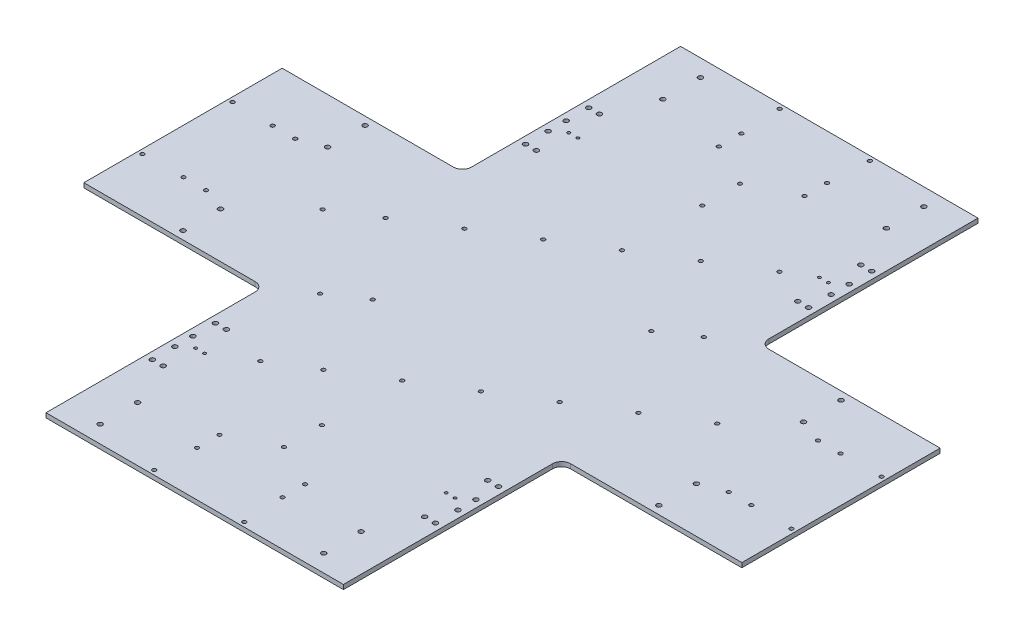
SolidWorks part; units mm, degrees
material "3.0205 (EN-AW 1200)"
ref_plane "前视基准面" through (0, 0, 0) normal (0, 0, 1) x (1, 0, 0)
ref_plane "上视基准面" through (0, 0, 0) normal (0, 1, 0) x (1, 0, 0)
ref_plane "右视基准面" through (0, 0, 0) normal (1, 0, 0) x (0, 0, -1)
other "Configuration Table"
sketch "Sketch1" plane through (0, 0, 0) normal (0, 1, 0) x (1, 0, 0)
  line L0 (165, 352) -> (-165, 352)
  line L1 (-165, 352) -> (-165, 110)
  line L2 (-165, 110) -> (-365, 110)
  line L5 (-365, 110) -> (-365, -110)
  line L6 (0, 352) -> (0, -66.8675) construction
  line L7 (-365, 0) -> (131.0517, 0) construction
  line L8 (365, 110) -> (365, -110)
  line L11 (165, 110) -> (365, 110)
  line L12 (165, 352) -> (165, 110)
  line L13 (165, -352) -> (165, -110)
  line L14 (165, -110) -> (365, -110)
  line L19 (-165, -110) -> (-365, -110)
  line L20 (-165, -352) -> (-165, -110)
  line L21 (165, -352) -> (-165, -352)
  point P21 (365, 0)
  dimension "D1" = 165
  dimension "D2" = 200
  dimension "D3" = 110
  dimension "D4" = 242
extrude "Boss-Extrude1" add sketch "Sketch1" along normal blind 5
sketch "Sketch2" plane through (0, 5, 0) normal (0, 1, 0) x (1, 0, 0)
  line L2 (365, 110) -> (165, 110) construction
  line L3 (365, -110) -> (365, 110) construction
  line L4 (-56.7455, 0) -> (47.5165, 0) construction
  line L5 (0, 54.7142) -> (0, -64.2255) construction
  line L7 (165, 352) -> (-165, 352) construction
  circle A0 centre (315, 49.5) radius 2.125
  circle A1 centre (290, 49.5) radius 2.125
  circle A7 centre (290, -49.5) radius 2.125
  circle A8 centre (315, -49.5) radius 2.125
  circle A9 centre (-315, -49.5) radius 2.125
  circle A10 centre (-290, -49.5) radius 2.125
  circle A13 centre (-290, 49.5) radius 2.125
  circle A14 centre (-315, 49.5) radius 2.125
  circle A15 centre (47.5, 302) radius 2.125
  circle A16 centre (47.5, 277) radius 2.125
  circle A17 centre (-47.5, 277) radius 2.125
  circle A18 centre (-47.5, 302) radius 2.125
  circle A19 centre (-47.5, -302) radius 2.125
  circle A20 centre (-47.5, -277) radius 2.125
  circle A21 centre (47.5, -277) radius 2.125
  circle A22 centre (47.5, -302) radius 2.125
  dimension "D1" = 60.5
  dimension "D5" = 4.25
  dimension "D7" = 4.25
  dimension "D9" = 4.25
  dimension "D10" = 4.25
  dimension "D4" = 25
  dimension "D6" = 50
  dimension "D11" = 47.5
  dimension "D12" = 50
  dimension "D13" = 25
extrude "Cut-Extrude1" cut sketch "Sketch2" against normal blind 3
sketch "Sketch4" plane through (0, 5, 0) normal (0, 1, 0) x (1, 0, 0)
  line L0 (-165, 352) -> (-165, 110) construction
  line L1 (165, 352) -> (-165, 352) construction
  line L2 (0, 46.9886) -> (0, -40.2904) construction
  line L3 (-35.103, 0) -> (92.4951, 0) construction
  line L5 (165, -352) -> (165, -110) construction
  circle A0 centre (-157, 172) radius 2.6
  circle A1 centre (-145, 172) radius 2.6
  circle A2 centre (-157, 197) radius 2.6
  circle A3 centre (-157, 217) radius 2.6
  circle A4 centre (-157, 242) radius 2.6
  circle A5 centre (-145, 242) radius 2.6
  circle A6 centre (145, 242) radius 2.6
  circle A7 centre (157, 242) radius 2.6
  circle A8 centre (157, 217) radius 2.6
  circle A9 centre (157, 197) radius 2.6
  circle A10 centre (145, 172) radius 2.6
  circle A11 centre (157, 172) radius 2.6
  circle A12 centre (157, -172) radius 2.6
  circle A13 centre (145, -172) radius 2.6
  circle A14 centre (157, -197) radius 2.6
  circle A15 centre (157, -217) radius 2.6
  circle A16 centre (157, -242) radius 2.6
  circle A17 centre (145, -242) radius 2.6
  circle A18 centre (-145, -242) radius 2.6
  circle A19 centre (-157, -242) radius 2.6
  circle A20 centre (-157, -217) radius 2.6
  circle A21 centre (-157, -197) radius 2.6
  circle A22 centre (-145, -172) radius 2.6
  circle A23 centre (-157, -172) radius 2.6
  circle A24 centre (144, -207) radius 1.6
  circle A25 centre (-144, -207) radius 1.6
  circle A26 centre (144, 207) radius 1.6
  circle A27 centre (-144, 207) radius 1.6
  circle A28 centre (134, -207) radius 1.6
  circle A29 centre (-134, -207) radius 1.6
  circle A30 centre (134, 207) radius 1.6
  circle A31 centre (-134, 207) radius 1.6
  dimension "D3" = 5.2
  dimension "D4" = 5.2
  dimension "D5" = 8
  dimension "D6" = 8
  dimension "D9" = 5.2
  dimension "D10" = 5.2
  dimension "D11" = 5.2
  dimension "D12" = 5.2
  dimension "D19" = 3.2
  dimension "D20" = 21
  dimension "D21" = 10
  dimension "D22" = 3.2
  dimension "D23" = 10
  dimension "D1" = 8
  dimension "D2" = 20
  dimension "D7" = 8
  dimension "D8" = 20
  dimension "D13" = 25
  dimension "D14" = 20
  dimension "D15" = 25
  dimension "D16" = 25
  dimension "D17" = 110
  dimension "D18" = 0
extrude "Cut-Extrude3" cut sketch "Sketch4" against normal blind 10
sketch "Sketch5" plane through (0, 5, 0) normal (0, 1, 0) x (1, 0, 0)
  line L0 (165, 352) -> (-165, 352) construction
  line L5 (-46.9195, 0) -> (66.6223, 0) construction
  line L6 (0, 59.0569) -> (0, -54.4849) construction
  line L10 (-365, 110) -> (-365, -110) construction
  line L12 (-165, 110) -> (-365, 110) construction
  line L13 (-365, -110) -> (-165, -110) construction
  circle A0 centre (-50, 347) radius 2.125
  circle A1 centre (50, 347) radius 2.125
  circle A2 centre (50, -347) radius 2.125
  circle A3 centre (-50, -347) radius 2.125
  circle A4 centre (-360, 50) radius 2.125
  circle A5 centre (-360, -50) radius 2.125
  circle A6 centre (360, -50) radius 2.125
  circle A7 centre (360, 50) radius 2.125
  dimension "D1" = 4.25
  dimension "D2" = 4.25
  dimension "D3" = 60
  dimension "D6" = 4.25
  dimension "D7" = 4.25
  dimension "5" = 5
  dimension "D4" = 50
  dimension "D5" = 50
  dimension "D8" = 60
  dimension "D9" = 5
  dimension "D10" = 5
extrude "Cut-Extrude4" cut sketch "Sketch5" against normal blind 10
fillet "Fillet1" radius 10 4 edges at (-165, 2.5, -110) (-165, 2.5, 110) (165, 2.5, 110) (165, 2.5, -110)
sketch "Sketch6" plane through (0, 5, 0) normal (0, 1, 0) x (1, 0, 0)
  line L0 (165, 352) -> (-165, 352) construction
  line L2 (165, 120) -> (165, 352) construction
  line L3 (-64.416, 0) -> (103.2752, 0) construction
  line L4 (0, 86.0771) -> (0, -73.7041) construction
  line L5 (365, 110) -> (175, 110) construction
  line L6 (365, -110) -> (365, 110) construction
  circle A0 centre (124, 333) radius 2.6
  circle A1 centre (124, 291.4) radius 2.6
  circle A2 centre (124, -291.4) radius 2.6
  circle A3 centre (124, -333) radius 2.6
  circle A4 centre (-124, -333) radius 2.6
  circle A5 centre (-124, -291.4) radius 2.6
  circle A6 centre (-124, 291.4) radius 2.6
  circle A7 centre (-124, 333) radius 2.6
  circle A8 centre (264, 101) radius 2.6
  circle A9 centre (264, 59.4) radius 2.6
  circle A10 centre (264, -59.4) radius 2.6
  circle A11 centre (264, -101) radius 2.6
  circle A12 centre (-264, -101) radius 2.6
  circle A13 centre (-264, -59.4) radius 2.6
  circle A14 centre (-264, 59.4) radius 2.6
  circle A15 centre (-264, 101) radius 2.6
  dimension "D1" = 5.2
  dimension "D2" = 5.2
  dimension "D6" = 5.2
  dimension "D7" = 5.2
  dimension "D3" = 19
  dimension "D4" = 41
  dimension "D5" = 41.6
  dimension "D8" = 9
  dimension "D9" = 41.6
  dimension "D10" = 101
extrude "Cut-Extrude5" cut sketch "Sketch6" against normal blind 10
sketch "Sketch7" plane through (0, 5, 0) normal (0, 1, 0) x (1, 0, 0)
  line L0 (197.463, 121.9013) -> (-168.3949, -103.9565) construction
  line L1 (180, 235.6925) -> (-379.973, -110) construction
  line L2 (144.6063, 226.5583) -> (333.7962, -79.9026) construction
  line L3 (-55.682, 90.1971) -> (55.682, -90.1971) construction
  line L4 (-167.9289, -112.9289) -> (167.9289, 112.9289) construction
  circle A0 centre (-55.682, 90.1971) radius 2.125
  circle A1 centre (-1.6489, 123.5538) radius 2.125
  circle A2 centre (52.3842, 156.9105) radius 2.125
  circle A3 centre (106.4174, 190.2672) radius 2.125
  circle A4 centre (-109.7152, 56.8404) radius 2.125
  circle A5 centre (-163.7483, 23.4837) radius 2.125
  circle A6 centre (-206.9749, -3.2017) radius 2.125
  circle A7 centre (-95.6108, -183.5958) radius 2.125
  circle A8 centre (-52.3842, -156.9105) radius 2.125
  circle A9 centre (1.6489, -123.5538) radius 2.125
  circle A10 centre (217.7815, 9.873) radius 2.125
  circle A11 centre (163.7483, -23.4837) radius 2.125
  circle A12 centre (109.7152, -56.8404) radius 2.125
  circle A13 centre (55.682, -90.1971) radius 2.125
  arc A14 (165, 120) -> (175, 110) centre (175, 120) ccw construction
  arc A15 (-165, -120) -> (-175, -110) centre (-175, -120) ccw construction
  point P35 (0, 0)
  point P36 (167.9289, 112.9289)
  point P37 (-167.9289, -112.9289)
  dimension "D1" = 4.25
  dimension "D2" = 4.25
  dimension "D3" = 4.25
  dimension "4.25" = 4.25
  dimension "D5" = 4.25
  dimension "D6" = 4.25
  dimension "D7" = 4.25
  dimension "D8" = 63.5
  dimension "D9" = 63.5
  dimension "D10" = 50.8
  dimension "D11" = 63.5
  dimension "D12" = 63.5
  dimension "D13" = 63.5
  dimension "D14" = 0
  dimension "D15" = 0
  dimension "D16" = 106
extrude "Cut-Extrude6" cut sketch "Sketch7" against normal blind 10
sketch "Sketch8" plane through (0, 5, 0) normal (0, 1, 0) x (1, 0, 0)
  line L0 (167.9289, 112.9289) -> (-167.9289, -112.9289) construction
  line L1 (81.1937, 116.467) -> (145.4556, 20.9075) construction
  line L2 (-135.7714, -35.3081) -> (-80.5576, -117.413) construction
  line L3 (0, 77.1364) -> (0, -65.7088) construction
  line L4 (-60.3124, 0) -> (69.2005, 0) construction
  line L5 (165, 352) -> (-165, 352) construction
  arc A0 (165, 120) -> (175, 110) centre (175, 120) ccw construction
  arc A1 (-165, -120) -> (-175, -110) centre (-175, -120) ccw construction
  circle A2 centre (-127.2679, -85.5852) radius 2.1
  circle A3 centre (-92.4156, -62.1477) radius 2.1
  circle A4 centre (92.4156, 62.1477) radius 2.1
  circle A5 centre (127.2679, 85.5852) radius 2.1
  circle A6 centre (0, 253) radius 2.1
  circle A7 centre (0, 211) radius 2.1
  circle A8 centre (0, -211) radius 2.1
  circle A9 centre (0, -253) radius 2.1
  dimension "D3" = 4.2
  dimension "D4" = 4.2
  dimension "D5" = 4.2
  dimension "D6" = 4.2
  dimension "D8" = 21
  dimension "D11" = 4.2
  dimension "D12" = 4.2
  dimension "D1" = 70
  dimension "D2" = 70
  dimension "D7" = 21
  dimension "D9" = 21
  dimension "D10" = 21
  dimension "D13" = 99
  dimension "D14" = 42
extrude "Cut-Extrude7" cut sketch "Sketch8" against normal blind 10
